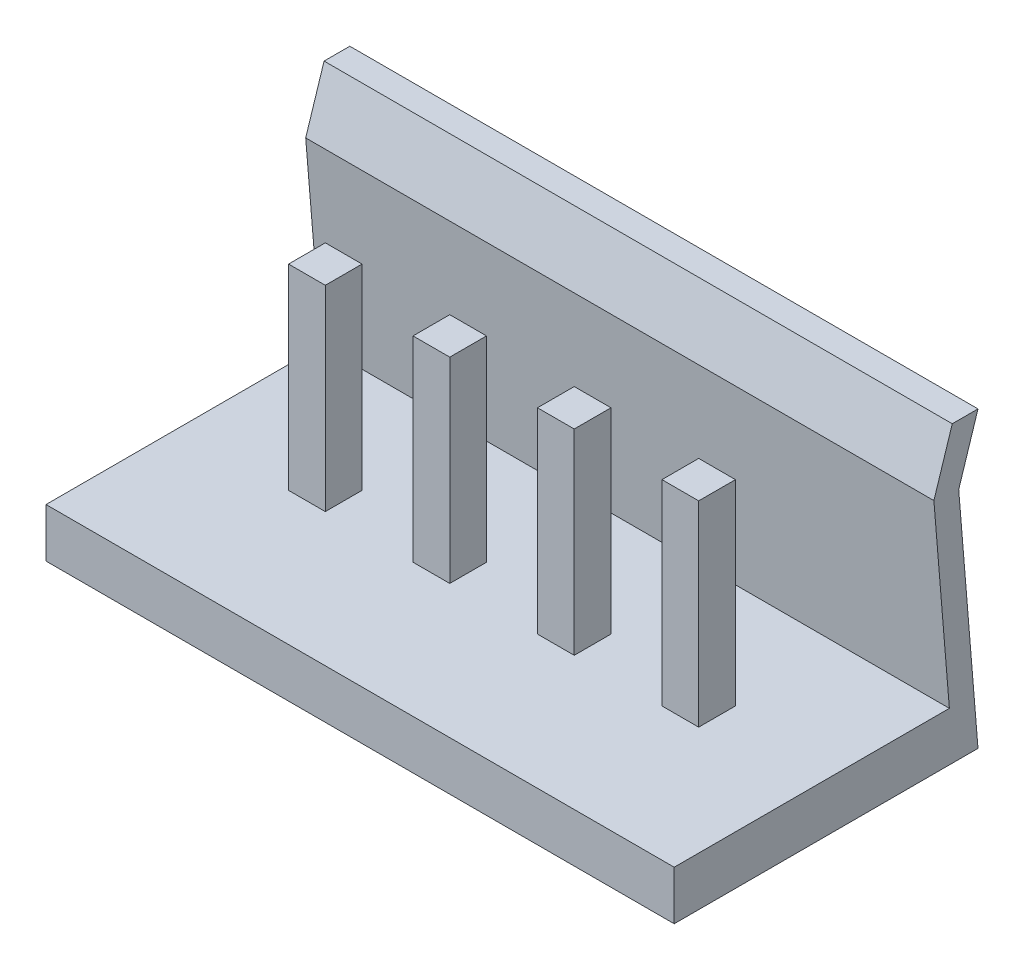
SolidWorks part; units mm, degrees
ref_plane "前视基准面" through (0, 0, 0) normal (0, 0, 1) x (1, 0, 0)
ref_plane "上视基准面" through (0, 0, 0) normal (0, 1, 0) x (1, 0, 0)
ref_plane "右视基准面" through (0, 0, 0) normal (1, 0, 0) x (0, 0, -1)
sketch "草图1" plane through (0, 0, 0) normal (0, 1, 0) x (1, 0, 0)
  line L0 (0, 7.1914) -> (0, -5.4429) construction
  line L1 (-6.41, 3.1) -> (6.41, 3.1)
  line L2 (-6.41, 3.1) -> (-6.41, -3.1)
  line L3 (-6.41, -3.1) -> (6.41, -3.1)
  line L4 (6.41, 3.1) -> (6.41, -3.1)
  line L5 (-10.6234, 0) -> (16.1963, 0) construction
  dimension "D1" = 12.82
  dimension "D2" = 6.2
extrude "拉伸1" add sketch "草图1" along normal blind 6
sketch "草图2" plane through (0, 6, 0) normal (0, 1, 0) x (-1, 0, 0)
  line L1 (6.41, -3.1) -> (6.41, 3.1) construction
  line L2 (-6.41, 3.1) -> (6.41, 3.1)
  line L3 (-6.41, 3.1) -> (-6.41, -2.1)
  line L4 (-6.41, -2.1) -> (6.41, -2.1)
  line L5 (6.41, 3.1) -> (6.41, -2.1)
  line L6 (-6.41, -3.1) -> (6.41, -3.1) construction
  dimension "D1" = 1
extrude "切除-拉伸1" cut sketch "草图2" against normal offset from surface (5 mm away) 1 up to face at (0, 0, 0)
sketch "草图5" plane through (-6.41, 0, 0) normal (-1, 0, 0) x (0, 0, 1)
  line L0 (-3.1, 6) -> (-2.7063, 4.7717)
  line L1 (-2.7063, 4.7717) -> (-3.1, 0)
  line L2 (-3.1, 0) -> (3.1, 0) construction
  line L3 (-3.1, 6) -> (-3.1, 0) construction
  line L9 (-3.1, 6) -> (-3.1, 0)
extrude "切除-拉伸2" cut sketch "草图5" against normal through all
sketch "草图6" plane through (-6.41, 0, 0) normal (-1, 0, 0) x (0, 0, 1)
  line L2 (-2.1, 1) -> (-2.1, 6) construction
  line L3 (-2.1, 1) -> (-2.1, 6)
  line L4 (-2.1998, 4.8296) -> (-2.6239, 6.1526)
  line L5 (-2.6017, -0.0411) -> (-2.1998, 4.8296)
  line L6 (-2.1998, 4.8296) -> (-2.5749, 6)
  line L7 (-2.5158, 1) -> (-2.1998, 4.8296)
  line L8 (-3.1, 6) -> (-2.1, 6) construction
  line L9 (-2.5749, 6) -> (-2.1, 6)
  line L10 (-2.1, 1) -> (-2.5158, 1)
  dimension "D1" = 0.5
extrude "切除-拉伸3" cut sketch "草图6" against normal through all
sketch "草图4" plane through (0, 0, 0) normal (0, -1, 0) x (1, 0, 0)
  line L0 (7.6775, 0) -> (-8.5467, 0) construction
  line L2 (0, -3.6953) -> (0, 4.0669) construction
  line L3 (-1.27, 1.5409) -> (-1.27, -1.2612) construction
  line L4 (-1.645, 0.375) -> (-0.895, 0.375)
  line L5 (-1.645, 0.375) -> (-1.645, -0.375)
  line L6 (-1.645, -0.375) -> (-0.895, -0.375)
  line L7 (-0.895, 0.375) -> (-0.895, -0.375)
  line L8 (0.895, 0.375) -> (1.645, 0.375)
  line L9 (0.895, 0.375) -> (0.895, -0.375)
  line L10 (0.895, -0.375) -> (1.645, -0.375)
  line L11 (1.645, 0.375) -> (1.645, -0.375)
  line L12 (3.435, 0.375) -> (4.185, 0.375)
  line L13 (3.435, 0.375) -> (3.435, -0.375)
  line L14 (3.435, -0.375) -> (4.185, -0.375)
  line L15 (4.185, 0.375) -> (4.185, -0.375)
  line L16 (-4.185, 0.375) -> (-3.435, 0.375)
  line L17 (-4.185, 0.375) -> (-4.185, -0.375)
  line L18 (-4.185, -0.375) -> (-3.435, -0.375)
  line L19 (-3.435, 0.375) -> (-3.435, -0.375)
  dimension "D2" = 0.75
  dimension "D3" = 0.75
  dimension "D4" = 1.27
extrude "拉伸2" add sketch "草图4" along normal blind 2 and the other way offset from surface (5 mm away) 1 other way up to face at (0, 6, -2.8375)
